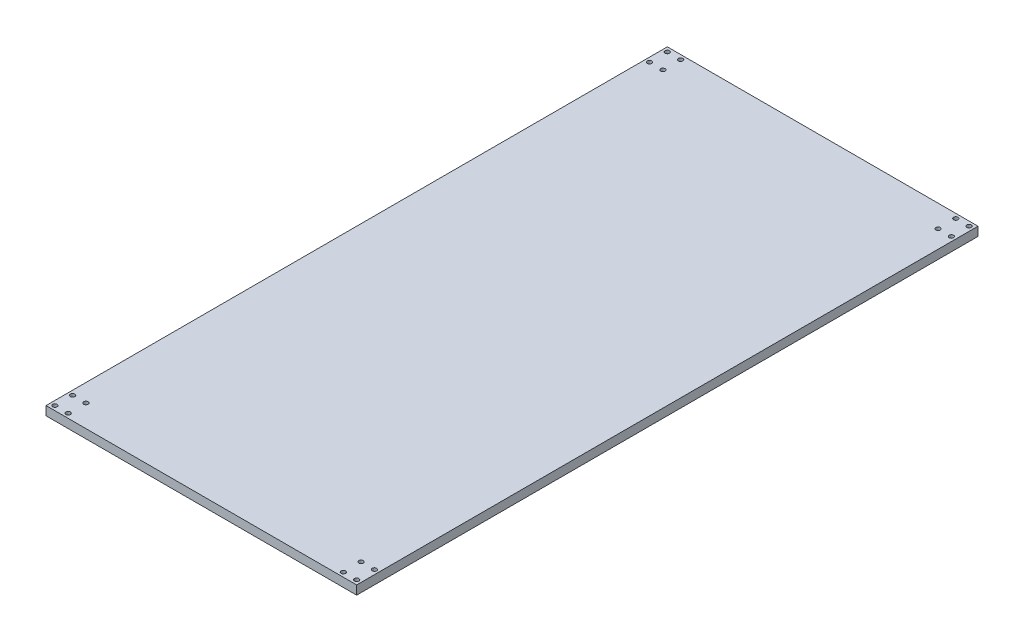
SolidWorks part; units mm, degrees
ref_plane "Спереди" through (0, 0, 0) normal (0, 0, 1) x (1, 0, 0)
ref_plane "Сверху" through (0, 0, 0) normal (0, 1, 0) x (1, 0, 0)
ref_plane "Справа" through (0, 0, 0) normal (1, 0, 0) x (0, 0, -1)
sketch "Эскиз1" plane through (0, 0, 0) normal (0, 1, 0) x (1, 0, 0)
  line L1 (-175, -350) -> (175, -350)
  line L2 (-175, -350) -> (-175, 350)
  line L3 (-175, 350) -> (175, 350)
  line L4 (175, -350) -> (175, 350)
  line L5 (0, 350) -> (0, -350) construction
  line L6 (-175, 0) -> (175, 0) construction
  line L7 (-155, -230) -> (155, -230) construction
  line L8 (-155, -230) -> (-155, 230) construction
  line L9 (-155, 230) -> (155, 230) construction
  line L10 (155, -230) -> (155, 230) construction
  line L11 (0, 230) -> (0, -230) construction
  line L12 (-155, 0) -> (155, 0) construction
  circle A0 centre (170, 345) radius 2.5
  circle A1 centre (155, 345) radius 2.5
  circle A2 centre (155, 325) radius 2.5
  circle A3 centre (170, 325) radius 2.5
  circle A4 centre (-170, 325) radius 2.5
  circle A5 centre (-155, 325) radius 2.5
  circle A6 centre (-155, 345) radius 2.5
  circle A7 centre (-170, 345) radius 2.5
  circle A8 centre (-170, -345) radius 2.5
  circle A9 centre (-155, -345) radius 2.5
  circle A10 centre (-155, -325) radius 2.5
  circle A11 centre (-170, -325) radius 2.5
  circle A12 centre (170, -325) radius 2.5
  circle A13 centre (155, -325) radius 2.5
  circle A14 centre (155, -345) radius 2.5
  circle A15 centre (170, -345) radius 2.5
  point P0 (0, 0)
  point P36 (0, 0)
  dimension "D4" = 5
  dimension "D1" = 350
  dimension "D2" = 700
  dimension "D3" = 5
  dimension "D5" = 5
  dimension "D8" = 15
  dimension "D9" = 155
  dimension "D10" = 325
  dimension "D11" = 310
  dimension "D12" = 460
  dimension "D6" = 2
  dimension "D7" = 2
extrude "Бобышка-Вытянуть1" add sketch "Эскиз1" along normal blind 10
